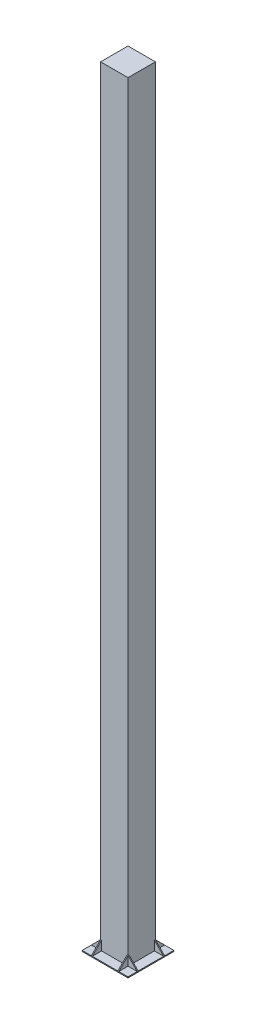
SolidWorks part; units mm, degrees
ref_plane "Alzado" through (0, 0, 0) normal (0, 0, 1) x (1, 0, 0)
ref_plane "Planta" through (0, 0, 0) normal (0, 1, 0) x (1, 0, 0)
ref_plane "Vista lateral" through (0, 0, 0) normal (1, 0, 0) x (0, 0, -1)
sketch "Croquis1" plane through (0, 0, 0) normal (0, 1, 0) x (1, 0, 0)
  line L1 (-177.8, -177.8) -> (177.8, -177.8)
  line L2 (-177.8, -177.8) -> (-177.8, 177.8)
  line L3 (-177.8, 177.8) -> (177.8, 177.8)
  line L4 (177.8, -177.8) -> (177.8, 177.8)
  line L5 (-177.8, -177.8) -> (177.8, 177.8) construction
  line L6 (-177.8, 177.8) -> (177.8, -177.8) construction
  point P0 (0, 0)
  dimension "D1" = 355.6
  dimension "D2" = 355.6
extrude "Saliente-Extruir1" add sketch "Croquis1" along normal blind 10000
sketch "Croquis2" plane through (0, 0, 0) normal (0, -1, 0) x (1, 0, 0)
  line L0 (-177.8, -177.8) -> (-177.8, 177.8) construction
  line L1 (297.8, 297.8) -> (-297.8, 297.8)
  line L2 (297.8, 297.8) -> (297.8, -297.8)
  line L3 (297.8, -297.8) -> (-297.8, -297.8)
  line L4 (-297.8, 297.8) -> (-297.8, -297.8)
  line L5 (297.8, 297.8) -> (-297.8, -297.8) construction
  line L6 (297.8, -297.8) -> (-297.8, 297.8) construction
  line L7 (177.8, -177.8) -> (-177.8, -177.8) construction
  point P0 (0, 0)
  point P8 (-177.8, 0)
  point P9 (-297.8, 0)
  dimension "D1" = 120
  dimension "D2" = 120
extrude "Saliente-Extruir2" add sketch "Croquis2" against normal blind 12.7
sketch "Croquis3" plane through (-177.8, 0, 0) normal (-1, 0, 0) x (0, 0, 1)
  line L0 (-297.8, 12.7) -> (-177.8, 132.7)
  line L1 (-177.8, 10000) -> (-177.8, 12.7) construction
  line L2 (-177.8, 132.7) -> (-177.8, 12.7)
  line L3 (-177.8, 12.7) -> (-297.8, 12.7)
extrude "Saliente-Extruir3" add sketch "Croquis3" against normal blind 12.7
sketch "Croquis4" plane through (177.8, 0, 0) normal (1, 0, 0) x (0, 0, -1)
  line L0 (177.8, 132.7) -> (297.8, 12.7)
  line L1 (297.8, 12.7) -> (177.8, 12.7)
  line L2 (177.8, 12.7) -> (177.8, 132.7)
extrude "Saliente-Extruir4" add sketch "Croquis4" against normal blind 12.7
sketch "Croquis5" plane through (0, 0, 177.8) normal (0, 0, 1) x (1, 0, 0)
  line L0 (297.8, 12.7) -> (177.8, 132.7)
  line L1 (177.8, 132.7) -> (177.8, 12.7)
  line L2 (177.8, 12.7) -> (297.8, 12.7)
extrude "Saliente-Extruir5" add sketch "Croquis5" against normal blind 12.7
sketch "Croquis6" plane through (0, 0, -177.8) normal (0, 0, -1) x (-1, 0, 0)
  line L0 (-177.8, 132.7) -> (-297.8, 12.7)
  line L1 (-297.8, 12.7) -> (-177.8, 12.7)
  line L2 (-177.8, 12.7) -> (-177.8, 132.7)
extrude "Saliente-Extruir6" add sketch "Croquis6" against normal blind 12.7
sketch "Croquis7" plane through (-177.8, 0, 0) normal (-1, 0, 0) x (0, 0, 1)
  line L0 (297.8, 12.7) -> (177.8, 132.7)
  line L1 (177.8, 132.7) -> (177.8, 12.7)
  line L2 (177.8, 12.7) -> (297.8, 12.7)
extrude "Saliente-Extruir7" add sketch "Croquis7" against normal blind 12.7
sketch "Croquis8" plane through (177.8, 0, 0) normal (1, 0, 0) x (0, 0, -1)
  line L0 (-177.8, 132.7) -> (-297.8, 12.7)
  line L1 (-297.8, 12.7) -> (-177.8, 12.7)
  line L2 (-177.8, 12.7) -> (-177.8, 132.7)
extrude "Saliente-Extruir8" add sketch "Croquis8" against normal blind 12.7
sketch "Croquis9" plane through (0, 0, -177.8) normal (0, 0, -1) x (-1, 0, 0)
  line L0 (297.8, 12.7) -> (177.8, 132.7)
  line L1 (177.8, 132.7) -> (177.8, 12.7)
  line L2 (177.8, 12.7) -> (297.8, 12.7)
extrude "Saliente-Extruir9" add sketch "Croquis9" against normal blind 12.7
sketch "Croquis10" plane through (0, 0, 177.8) normal (0, 0, 1) x (1, 0, 0)
  line L0 (-297.8, 12.7) -> (-177.8, 132.7)
  line L1 (-177.8, 132.7) -> (-177.8, 12.7)
  line L2 (-177.8, 12.7) -> (-297.8, 12.7)
extrude "Saliente-Extruir10" add sketch "Croquis10" against normal blind 12.7
